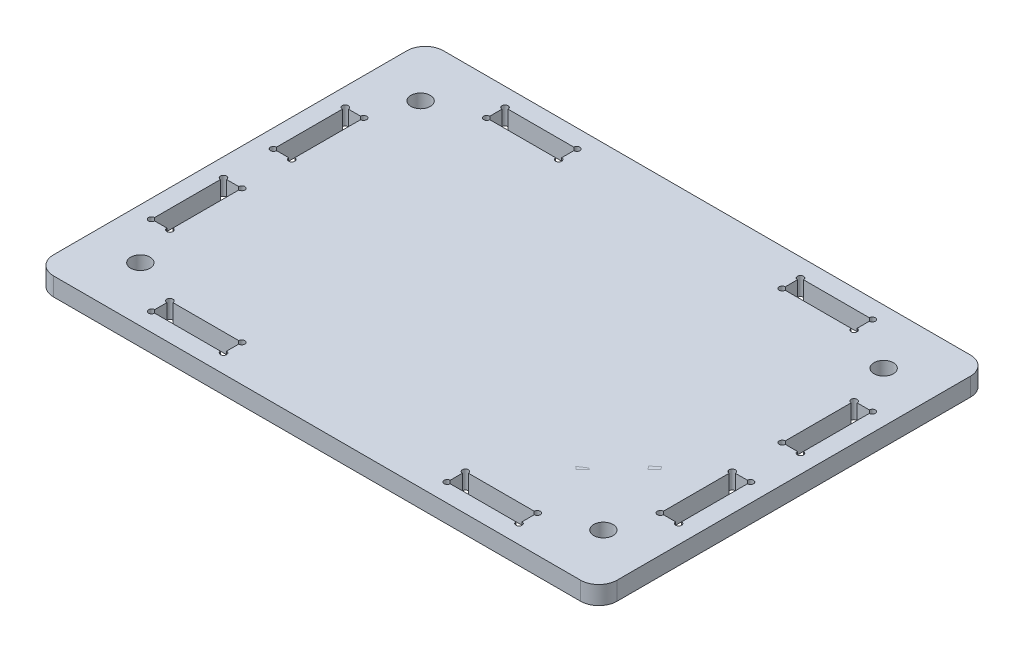
SolidWorks part; units mm, degrees
material "Acrylic (Medium-high impact)"
ref_plane "Front Plane" through (0, 0, 0) normal (0, 0, 1) x (1, 0, 0)
ref_plane "Top Plane" through (0, 0, 0) normal (0, 1, 0) x (1, 0, 0)
ref_plane "Right Plane" through (0, 0, 0) normal (1, 0, 0) x (0, 0, -1)
sketch "Sketch5" plane through (0, 0, 0) normal (0, 1, 0) x (1, 0, 0)
  line L0 (20, 50) -> (20, 0) construction
  line L1 (0, 0) -> (80, 0) construction
  line L2 (0, 0) -> (0, 50) construction
  line L3 (0, 50) -> (80, 50) construction
  line L4 (80, 0) -> (80, 50) construction
  line L9 (-3.25, -7) -> (83.25, -7)
  line L10 (-6.25, -4) -> (-6.25, 54)
  line L11 (-3.25, 57) -> (83.25, 57)
  line L12 (86.25, -4) -> (86.25, 54)
  line L13 (40, 50) -> (40, 0) construction
  line L14 (60, 50) -> (60, 0) construction
  line L15 (0, 25) -> (80, 25) construction
  circle A0 centre (2, 2) radius 1.5875
  circle A1 centre (2, 48) radius 1.5875
  circle A2 centre (78, 48) radius 1.5875
  circle A3 centre (78, 2) radius 1.5875
  arc A4 (-6.25, -4) -> (-3.25, -7) centre (-3.25, -4) ccw
  arc A5 (-3.25, 57) -> (-6.25, 54) centre (-3.25, 54) ccw
  arc A6 (86.25, 54) -> (83.25, 57) centre (83.25, 54) ccw
  arc A7 (83.25, -7) -> (86.25, -4) centre (83.25, -4) ccw
  line B0 (10.3533, 54) -> (21.1533, 54)
  line B1 (9.8533, 53.5) -> (9.8533, 51.5)
  line B2 (10.3533, 51) -> (21.1533, 51)
  line B3 (21.6533, 53.5) -> (21.6533, 51.5)
  arc B4 (10.3533, 54) -> (9.8533, 53.5) centre (9.8533, 54) ccw
  arc B5 (9.8533, 51.5) -> (10.3533, 51) centre (9.8533, 51) ccw
  arc B6 (21.6533, 53.5) -> (21.1533, 54) centre (21.6533, 54) ccw
  arc B7 (21.1533, 51) -> (21.6533, 51.5) centre (21.6533, 51) ccw
  line B8 (58.85, 54) -> (69.65, 54)
  line B9 (58.35, 53.5) -> (58.35, 51.5)
  line B10 (58.85, 51) -> (69.65, 51)
  line B11 (70.15, 53.5) -> (70.15, 51.5)
  arc B12 (58.85, 54) -> (58.35, 53.5) centre (58.35, 54) ccw
  arc B13 (58.35, 51.5) -> (58.85, 51) centre (58.35, 51) ccw
  arc B14 (70.15, 53.5) -> (69.65, 54) centre (70.15, 54) ccw
  arc B15 (69.65, 51) -> (70.15, 51.5) centre (70.15, 51) ccw
  line B16 (10.35, -1) -> (21.15, -1)
  line B17 (9.85, -1.5) -> (9.85, -3.5)
  line B18 (10.35, -4) -> (21.15, -4)
  line B19 (21.65, -1.5) -> (21.65, -3.5)
  arc B20 (10.35, -1) -> (9.85, -1.5) centre (9.85, -1) ccw
  arc B21 (9.85, -3.5) -> (10.35, -4) centre (9.85, -4) ccw
  arc B22 (21.65, -1.5) -> (21.15, -1) centre (21.65, -1) ccw
  arc B23 (21.15, -4) -> (21.65, -3.5) centre (21.65, -4) ccw
  line B24 (58.85, -1) -> (69.65, -1)
  line B25 (58.35, -1.5) -> (58.35, -3.5)
  line B26 (58.85, -4) -> (69.65, -4)
  line B27 (70.15, -1.5) -> (70.15, -3.5)
  arc B28 (58.85, -1) -> (58.35, -1.5) centre (58.35, -1) ccw
  arc B29 (58.35, -3.5) -> (58.85, -4) centre (58.35, -4) ccw
  arc B30 (70.15, -1.5) -> (69.65, -1) centre (70.15, -1) ccw
  arc B31 (69.65, -4) -> (70.15, -3.5) centre (70.15, -4) ccw
  line B32 (-3.25, 9.6) -> (-3.25, 20.4)
  line B33 (-2.75, 9.1) -> (-0.75, 9.1)
  line B34 (-0.25, 9.6) -> (-0.25, 20.4)
  line B35 (-2.75, 20.9) -> (-0.75, 20.9)
  arc B36 (-3.25, 9.6) -> (-2.75, 9.1) centre (-3.25, 9.1) ccw
  arc B37 (-0.75, 9.1) -> (-0.25, 9.6) centre (-0.25, 9.1) ccw
  arc B38 (-2.75, 20.9) -> (-3.25, 20.4) centre (-3.25, 20.9) ccw
  arc B39 (-0.25, 20.4) -> (-0.75, 20.9) centre (-0.25, 20.9) ccw
  line B40 (-3.25, 29.6) -> (-3.25, 40.4)
  line B41 (-2.75, 29.1) -> (-0.75, 29.1)
  line B42 (-0.25, 29.6) -> (-0.25, 40.4)
  line B43 (-2.75, 40.9) -> (-0.75, 40.9)
  arc B44 (-3.25, 29.6) -> (-2.75, 29.1) centre (-3.25, 29.1) ccw
  arc B45 (-0.75, 29.1) -> (-0.25, 29.6) centre (-0.25, 29.1) ccw
  arc B46 (-2.75, 40.9) -> (-3.25, 40.4) centre (-3.25, 40.9) ccw
  arc B47 (-0.25, 40.4) -> (-0.75, 40.9) centre (-0.25, 40.9) ccw
  line B48 (80.25, 9.6) -> (80.25, 20.4)
  line B49 (80.75, 9.1) -> (82.75, 9.1)
  line B50 (83.25, 9.6) -> (83.25, 20.4)
  line B51 (80.75, 20.9) -> (82.75, 20.9)
  arc B52 (80.25, 9.6) -> (80.75, 9.1) centre (80.25, 9.1) ccw
  arc B53 (82.75, 9.1) -> (83.25, 9.6) centre (83.25, 9.1) ccw
  arc B54 (80.75, 20.9) -> (80.25, 20.4) centre (80.25, 20.9) ccw
  arc B55 (83.25, 20.4) -> (82.75, 20.9) centre (83.25, 20.9) ccw
  line B56 (80.25, 29.6) -> (80.25, 40.4)
  line B57 (80.75, 29.1) -> (82.75, 29.1)
  line B58 (83.25, 29.6) -> (83.25, 40.4)
  line B59 (80.75, 40.9) -> (82.75, 40.9)
  arc B60 (80.25, 29.6) -> (80.75, 29.1) centre (80.25, 29.1) ccw
  arc B61 (82.75, 29.1) -> (83.25, 29.6) centre (83.25, 29.1) ccw
  arc B62 (80.75, 40.9) -> (80.25, 40.4) centre (80.25, 40.9) ccw
  arc B63 (83.25, 40.4) -> (82.75, 40.9) centre (83.25, 40.9) ccw
  dimension "D1" = 80
  dimension "D2" = 50
  dimension "D43" = 16.1
  dimension "D15" = 3.175
  dimension "D12" = 3.175
  dimension "D18" = 3.175
  dimension "D21" = 6.25
  dimension "D27" = 3
  dimension "D29" = 64
  dimension "D38" = 3
  dimension "D40" = 3
  dimension "D39" = 16.1
  dimension "D46" = 3
  dimension "D49" = 20
  dimension "D7" = 3.175
  dimension "D13" = 2
  dimension "D23" = 3
  dimension "D20" = 3
  dimension "D19" = 3
  dimension "D33" = 16.1
  dimension "D37" = 16.1
  dimension "D34" = 3
  dimension "D35" = 16.1
  dimension "D36" = 3
  dimension "D8" = 2
  dimension "D9" = 2
  dimension "D10" = 2
  dimension "D11" = 2
  dimension "D14" = 2
  dimension "D16" = 2
  dimension "D17" = 2
  dimension "D24" = 3
  dimension "D25" = 3
  dimension "D26" = 3
  dimension "D28" = 3
  dimension "D30" = 92.5
  dimension "D31" = 16.1033
  dimension "D32" = 3
  dimension "D41" = 3
  dimension "D42" = 16.1
  dimension "D44" = 3
  dimension "D45" = 16.1
  dimension "D47" = 20
  dimension "D48" = 20
sketch_block_instance "Block2-1"
sketch_block "Block2" parameters "D3"=0.5, "D4"=0.5, "D5"=0.5, "D6"=0.5, "D1"=10.8, "D2"=2, "D7"=10.8, "D8"=2, "D9"=11.8, "D10"=3, "D11"=3, "D12"=11.8
sketch_block_instance "Block2-2"
sketch_block_instance "Block2-3"
sketch_block_instance "Block2-4"
sketch_block_instance "Block2-5"
sketch_block_instance "Block2-6"
sketch_block_instance "Block2-7"
sketch_block_instance "Block2-8"
extrude "Boss-Extrude1" add sketch "Sketch5" along normal blind 3
sketch "Sketch6" plane through (0, 3, 0) normal (0, 1, 0) x (1, 0, 0)
  line L0 (6.25, 4.0625) -> (10, 11.5625)
  line L1 (40, 50) -> (40, 0) construction
  line L2 (6.25, 20.9375) -> (13.75, 20.9375)
  line L3 (6.25, 20.9375) -> (6.25, 19.0625)
  line L4 (6.25, 4.0625) -> (13.75, 4.0625)
  line L5 (13.75, 20.9375) -> (13.75, 19.0625)
  line L6 (10, 11.5625) -> (13.75, 4.0625)
  line L7 (6.25, 19.0625) -> (13.75, 19.0625)
  line L8 (13.75, 17.1875) -> (6.25, 17.1875)
  line L9 (6.25, 15.3125) -> (13.75, 15.3125)
  line L10 (0, 0) -> (0, 50) construction
  line L11 (0, 50) -> (80, 50) construction
  line L12 (0, 25) -> (80, 25) construction
  line L13 (6.25, 17.1875) -> (6.25, 15.3125)
  line L14 (13.75, 17.1875) -> (13.75, 15.3125)
  line L15 (20, 50) -> (20, 0) construction
  line L16 (0, 0) -> (80, 0) construction
  line L17 (26.25, 29.0625) -> (30, 36.5625)
  line L18 (26.25, 45.9375) -> (33.75, 45.9375)
  line L19 (26.25, 45.9375) -> (26.25, 44.0625)
  line L20 (26.25, 29.0625) -> (33.75, 29.0625)
  line L21 (33.75, 45.9375) -> (33.75, 44.0625)
  line L22 (30, 36.5625) -> (33.75, 29.0625)
  line L23 (26.25, 44.0625) -> (33.75, 44.0625)
  line L24 (26.25, 36.5625) -> (33.75, 36.5625)
  line L25 (33.75, 36.5625) -> (30, 44.0625)
  line L26 (30, 44.0625) -> (26.25, 36.5625)
  line L27 (33.75, 20.9375) -> (30, 13.4375)
  line L28 (33.75, 4.0625) -> (26.25, 4.0625)
  line L29 (33.75, 4.0625) -> (33.75, 5.9375)
  line L30 (33.75, 20.9375) -> (26.25, 20.9375)
  line L31 (26.25, 4.0625) -> (26.25, 5.9375)
  line L32 (30, 13.4375) -> (26.25, 20.9375)
  line L33 (33.75, 5.9375) -> (26.25, 5.9375)
  line L34 (33.75, 13.4375) -> (26.25, 13.4375)
  line L35 (26.25, 13.4375) -> (30, 5.9375)
  line L36 (30, 5.9375) -> (33.75, 13.4375)
  line L37 (48, 32.64) -> (45, 36.0627)
  line L38 (6.25, 33.75) -> (13.75, 33.75)
  line L39 (6.25, 33.75) -> (6.25, 41.25)
  line L40 (6.25, 41.25) -> (13.75, 41.25)
  line L41 (13.75, 33.75) -> (13.75, 41.25)
  line L43 (48, 10.5) -> (45, 13.9227)
  line L44 (48, 8.5) -> (52, 8.5)
  line L45 (48, 8.5) -> (48, 10.5)
  line L46 (48, 30.64) -> (52, 30.64)
  line L47 (48, 30.64) -> (48, 32.64)
  line L48 (52, 8.5) -> (52, 10.5)
  line L49 (52, 30.64) -> (52, 32.64)
  line L50 (45, 36.0627) -> (55, 36.0627)
  line L51 (55, 36.0627) -> (52, 32.64)
  line L52 (45, 13.9227) -> (55, 13.9227)
  line L53 (55, 13.9227) -> (52, 10.5)
  line L54 (50.0038, 16.3533) -> (52.35, 16.3533)
  line L55 (60, 50) -> (60, 0) construction
  line L56 (70, 9) -> (70, 7.5)
  line L57 (67.2404, 16.6695) -> (66.8264, 17.2949)
  line L58 (70, 17.5) -> (70, 16)
  line L60 (71.9318, 9.5814) -> (71.5178, 10.2068)
  line L61 (68.0682, 15.4186) -> (68.4822, 14.7932)
  line L62 (72.7596, 8.3305) -> (73.1736, 7.7051)
  line L65 (71.5178, 10.2068) -> (71.0949, 8.1281)
  line L66 (71.0949, 8.1281) -> (73.1736, 7.7051)
  line L68 (66.8264, 17.2949) -> (68.9051, 16.8719)
  line L69 (68.9051, 16.8719) -> (68.4822, 14.7932)
  arc A0 (47.65, 37.4971) -> (48.35, 36.7829) centre (48, 37.14) ccw
  arc A1 (51.65, 36.7654) -> (52.35, 37.4795) centre (52, 37.1225) ccw
  arc A2 (47.65, 37.4971) -> (52.35, 37.4795) centre (49.9916, 35.2433) cw
  arc A3 (48.35, 36.7829) -> (51.65, 36.7654) centre (49.9919, 35.2445) cw
  arc A4 (46.65, 39.9971) -> (47.35, 39.2829) centre (47, 39.64) ccw
  arc A5 (52.65, 39.2654) -> (53.35, 39.9795) centre (53, 39.6225) ccw
  arc A6 (46.65, 39.9971) -> (53.35, 39.9795) centre (49.9912, 36.6208) cw
  arc A7 (47.35, 39.2829) -> (52.65, 39.2654) centre (49.9912, 36.6209) cw
  arc A8 (45.65, 42.4971) -> (46.35, 41.7829) centre (46, 42.14) ccw
  arc A9 (53.65, 41.7654) -> (54.35, 42.4795) centre (54, 42.1225) ccw
  arc A10 (46.35, 41.7829) -> (53.65, 41.7654) centre (49.9918, 38.3569) cw
  arc A11 (45.65, 42.4971) -> (54.35, 42.4795) centre (49.9917, 38.3558) cw
  arc A12 (47.65, 15.3571) -> (48.35, 14.6429) centre (48, 15) ccw
  arc A13 (51.65, 14.6254) -> (52.35, 15.3395) centre (52, 14.9825) ccw
  arc A14 (47.65, 15.3571) -> (52.35, 15.3395) centre (49.9916, 13.1033) cw
  arc A15 (48.35, 14.6429) -> (51.65, 14.6254) centre (49.9919, 13.1045) cw
  circle A16 centre (70, 37.5) radius 3.5
  circle A17 centre (70, 37.5) radius 2
  circle A18 centre (70, 37.5) radius 5
  arc A19 (68.0682, 15.4186) -> (70, 9) centre (70, 12.5) ccw
  arc A20 (71.9318, 9.5814) -> (70, 16) centre (70, 12.5) ccw
  arc A21 (67.2404, 16.6695) -> (70, 7.5) centre (70, 12.5) ccw
  arc A22 (72.7596, 8.3305) -> (70, 17.5) centre (70, 12.5) ccw
  dimension "D46" = 0.35
  dimension "D50" = 1
  dimension "D51" = 1
  dimension "D55" = 2.25
  dimension "D56" = 3.25
  dimension "D44" = 1
  dimension "D57" = 1
  dimension "D58" = 1
  dimension "D59" = 0.35
  dimension "D64" = 4.75
  dimension "D65" = 3.75
  dimension "D70" = 2.5
  dimension "D71" = 2.5
  dimension "D73" = 2
  dimension "D74" = 0.35
  dimension "D66" = 1
  dimension "D67" = 1
  dimension "D78" = 6
  dimension "D79" = 5
  dimension "D88" = 1
  dimension "D89" = 1
  dimension "D92" = 2.25
  dimension "D93" = 3.25
  dimension "D100" = 4
  dimension "D101" = 7
  dimension "D102" = 10
  dimension "D103" = 12.5
  dimension "D98" = 10
  dimension "D99" = 7
  dimension "D104" = 10
  dimension "D1" = 6.25
  dimension "D2" = 7.5
  dimension "D3" = 7.5
  dimension "D4" = 1.875
  dimension "D5" = 1.875
  dimension "D6" = 1.875
  dimension "D7" = 6.25
  dimension "D8" = 4.0625
  dimension "D9" = 6.25
  dimension "D10" = 4.0625
  dimension "D11" = 10
  dimension "D12" = 7.5
  dimension "D13" = 7.5
  dimension "D14" = 1.875
  dimension "D15" = 0
  dimension "D16" = 7.5
  dimension "D17" = 7.5
  dimension "D18" = 0
  dimension "D19" = 0
  dimension "D20" = 7.5
  dimension "D21" = 4.0625
  dimension "D22" = 6.25
  dimension "D23" = 7.5
  dimension "D24" = 7.5
  dimension "D25" = 1.875
  dimension "D26" = 3.75
  dimension "D27" = 7.5
  dimension "D28" = 7.5
  dimension "D29" = 7.5
  dimension "D30" = 0
  dimension "D31" = 0
  dimension "D32" = 6.25
  dimension "D33" = 4.0625
  dimension "D34" = 8.5
  dimension "D35" = 5
  dimension "D36" = 7.5
  dimension "D37" = 7.5
  dimension "D38" = 6.25
  dimension "D39" = 8.75
  dimension "D40" = 5.64
  dimension "D41" = 3
  dimension "D42" = 4
  dimension "D43" = 2
  dimension "D45" = 3
  dimension "D47" = 0.35
  dimension "D48" = 0.35
  dimension "D49" = 0.35
  dimension "D52" = 4.5
  dimension "D53" = 4
  dimension "D54" = 1
  dimension "D60" = 8
  dimension "D61" = 0.35
  dimension "D62" = 0.35
  dimension "D63" = 0.35
  dimension "D68" = 2.5
  dimension "D69" = 2.5
  dimension "D72" = 6
  dimension "D75" = 0.35
  dimension "D76" = 0.35
  dimension "D77" = 0.35
  dimension "D80" = 5
  dimension "D81" = 3
  dimension "D82" = 4
  dimension "D83" = 2
  dimension "D84" = 0.35
  dimension "D85" = 0.35
  dimension "D86" = 0.35
  dimension "D87" = 0.35
  dimension "D90" = 4.5
  dimension "D91" = 4
  dimension "D96" = 10
  dimension "D97" = 12.5
  dimension "D105" = 0.75
  dimension "D106" = 0.75
  dimension "D107" = 0.75
  dimension "D108" = 0.75
  dimension "D114" = 3
  dimension "D115" = 3
  dimension "D120" = 2
  dimension "D121" = 3
extrude "Boss-Extrude2" add sketch "Sketch6" against normal blind 0.2 separate body contours A18 A16 | A17 | L62 A22 L58 A20 L60 L65 L66 | L57 A21 L56 A19 L61 L69 L68 | L51 L50 L37 L47 L46 L49 | A0 A3 A1 A2 | A4 A7 A5 A6 | A11 A8 A10 A9 | L53 L52 L43 L45 L44 L48 | A12 A15 A13 A14 | L25 L26 L24 | L19 L23 L21 L18 | L22 L17 L20 | L32 L27 L30 | L35 L36 L34 | L29 L33 L31 L28 | L6 L0 L4 | L14 L8 L13 L9 | L3 L7 L5 L2 | L38 L41 L40 L39
